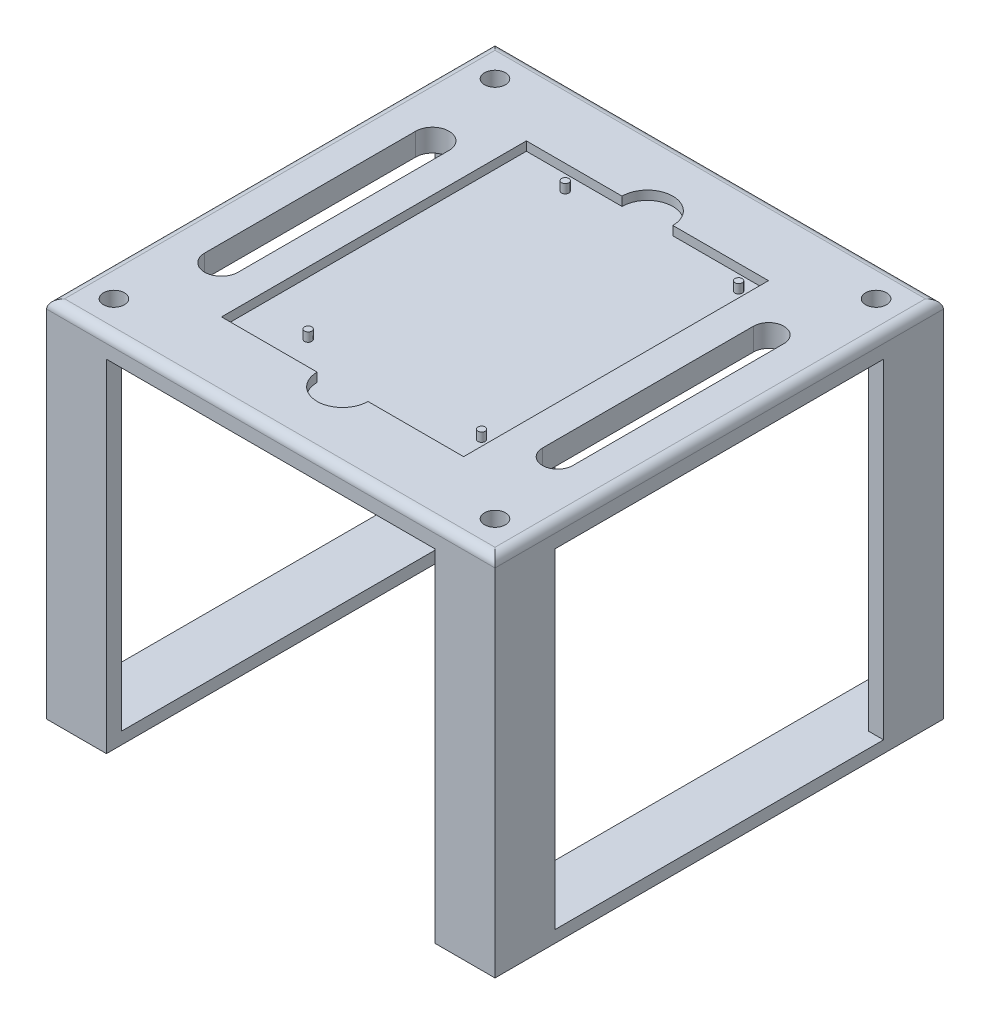
SolidWorks part; units mm, degrees
ref_plane "Front Plane" through (0, 0, 0) normal (0, 0, 1) x (1, 0, 0)
ref_plane "Top Plane" through (0, 0, 0) normal (0, 1, 0) x (1, 0, 0)
ref_plane "Right Plane" through (0, 0, 0) normal (1, 0, 0) x (0, 0, -1)
sketch "Sketch1" plane through (0, 0, 0) normal (0, 1, 0) x (1, 0, 0)
  line L1 (-75, 75) -> (75, 75)
  line L2 (-75, 75) -> (-75, -75)
  line L3 (-75, -75) -> (75, -75)
  line L4 (75, 75) -> (75, -75)
  line L5 (-75, 75) -> (75, -75) construction
  line L6 (-75, -75) -> (75, 75) construction
  point P0 (0, 0)
extrude "Boss-Extrude1" add sketch "Sketch1" along normal blind 7.5
sketch "Sketch2" plane through (0, 0, 0) normal (0, -1, 0) x (1, 0, 0)
  line L0 (-75, 70) -> (-70, 70) construction
  line L13 (-75, 75) -> (-55, 75)
  line L14 (-75, 75) -> (-75, 55)
  line L21 (-75, 55) -> (-70, 55)
  line L22 (-70, 55) -> (-70, 70)
  line L23 (-70, 70) -> (-55, 70)
  line L24 (-55, 70) -> (-55, 75)
  line L25 (75, 75) -> (54.9562, 75)
  line L26 (-75, 75) -> (75, 75) construction
  line L27 (54.9562, 75) -> (54.9562, 70)
  line L28 (54.9562, 70) -> (69.9502, 70)
  line L29 (69.9502, 70) -> (69.9502, 55)
  line L30 (69.9502, 55) -> (75, 55)
  line L31 (75, 75) -> (75, -75) construction
  line L32 (75, 55) -> (75, 75)
  line L33 (-75, -75) -> (-55, -75)
  line L34 (75, -75) -> (-75, -75) construction
  line L35 (-55, -75) -> (-55, -69.9766)
  line L36 (-55, -69.9766) -> (-70, -69.9766)
  line L37 (-70, -69.9766) -> (-70, -55.0007)
  line L38 (-70, -55.0007) -> (-75, -55.0007)
  line L39 (-75, -75) -> (-75, 75) construction
  line L40 (-75, -55.0007) -> (-75, -75)
  line L41 (75, -75) -> (54.9562, -75)
  line L42 (54.9562, -75) -> (54.9562, -69.9766)
  line L43 (54.9562, -69.9766) -> (69.9502, -69.9766)
  line L44 (69.9502, -69.9766) -> (69.9502, -55.0007)
  line L45 (69.9502, -55.0007) -> (75, -55.0007)
  line L46 (75, -55.0007) -> (75, -75)
extrude "Boss-Extrude2" add sketch "Sketch2" along normal blind 114.3
fillet "Fillet1" radius 3 4 edges at (0, 7.5, 75) (-75, 7.5, 0) (0, 7.5, -75) (75, 7.5, 0)
sketch "Sketch3" plane through (0, -114.3, 0) normal (0, -1, 0) x (1, 0, 0)
  line L17 (75, -75) -> (54.9562, -75)
  line L18 (75, -75) -> (75, 75)
  line L19 (75, 75) -> (54.9562, 75)
  line L20 (54.9562, -75) -> (54.9562, 75)
  line L21 (-75, 75) -> (-55, 75)
  line L22 (-75, 75) -> (-75, -75)
  line L23 (-75, -75) -> (-55, -75)
  line L24 (-55, 75) -> (-55, -75)
extrude "Boss-Extrude3" add sketch "Sketch3" against normal blind 4
sketch "Sketch5" plane through (0, 7.5, 0) normal (0, 1, 0) x (1, 0, 0)
  line L1 (-40.5, 51) -> (40.5, 51)
  line L2 (-40.5, 51) -> (-40.5, -51)
  line L3 (-40.5, -51) -> (40.5, -51)
  line L4 (40.5, 51) -> (40.5, -51)
  line L5 (-40.5, 51) -> (40.5, -51) construction
  line L6 (-40.5, -51) -> (40.5, 51) construction
  point P0 (0, 0)
extrude "Cut-Extrude1" cut sketch "Sketch5" against normal blind 3
sketch "Sketch6" plane through (0, 7.5, 0) normal (0, 1, 0) x (1, 0, 0)
  line L0 (-40.5, 0) -> (-72, 0) construction
  line L1 (-40.5, 51) -> (-40.5, -51) construction
  line L2 (-72, 72) -> (-72, -72) construction
  line L3 (-56.25, 35.2997) -> (-56.25, -35.2997) construction
  line L4 (-50.6741, 35.2997) -> (-50.6741, -35.2997)
  line L5 (-61.8259, 35.2997) -> (-61.8259, -35.2997)
  line L6 (40.5, 0) -> (72, 0) construction
  line L7 (40.5, -51) -> (40.5, 51) construction
  line L8 (72, -72) -> (72, 72) construction
  line L9 (56.25, 35.2997) -> (56.25, -35.2997) construction
  line L10 (61.3259, 35.2997) -> (61.3259, -35.2997)
  line L11 (51.1741, 35.2997) -> (51.1741, -35.2997)
  arc A0 (-50.6741, 35.2997) -> (-61.8259, 35.2997) centre (-56.25, 35.2997) ccw
  arc A1 (-61.8259, -35.2997) -> (-50.6741, -35.2997) centre (-56.25, -35.2997) ccw
  arc A2 (61.3259, 35.2997) -> (51.1741, 35.2997) centre (56.25, 35.2997) ccw
  arc A3 (51.1741, -35.2997) -> (61.3259, -35.2997) centre (56.25, -35.2997) ccw
  point P8 (-56.25, 0)
  point P21 (56.25, 0)
extrude "Cut-Extrude3" cut sketch "Sketch6" against normal up to next
sketch "Sketch7" plane through (0, 4.5, 0) normal (0, 1, 0) x (1, 0, 0)
  line L0 (39.5, 50) -> (39.5, 46) construction
  line L5 (39.5, 46) -> (35.5, 46) construction
  line L6 (-39.5, 50) -> (39.5, 50) construction
  line L7 (-39.5, 50) -> (-39.5, -50) construction
  line L8 (-39.5, -50) -> (39.5, -50) construction
  line L9 (39.5, 50) -> (39.5, -50) construction
  line L10 (35.5, 46) -> (-22.5, 46) construction
  line L11 (35.5, 46) -> (35.5, -40) construction
  line L12 (35.5, -40) -> (-22.5, -40) construction
  circle A0 centre (35.5, 46) radius 1.225
  circle A1 centre (-22.5, 46) radius 1.225
  circle A2 centre (-22.5, -40) radius 1.225
  circle A3 centre (35.5, -40) radius 1.225
  point P0 (0, 0)
  dimension "D1" = 4
extrude "Boss-Extrude4" add sketch "Sketch7" along normal blind 3
sketch "Sketch8" plane through (0, 7.5, 0) normal (0, 1, 0) x (1, 0, 0)
  line L1 (-63.75, 63.75) -> (63.75, 63.75) construction
  line L2 (-63.75, 63.75) -> (-63.75, -63.75) construction
  line L3 (-63.75, -63.75) -> (63.75, -63.75) construction
  line L4 (63.75, 63.75) -> (63.75, -63.75) construction
  line L5 (-63.75, 63.75) -> (63.75, -63.75) construction
  line L6 (-63.75, -63.75) -> (63.75, 63.75) construction
  circle A0 centre (-63.75, -63.75) radius 3.5
  circle A1 centre (63.75, -63.75) radius 3.5
  circle A2 centre (-63.75, 63.75) radius 3.5
  circle A3 centre (63.75, 63.75) radius 3.5
  point P0 (0, 0)
extrude "Cut-Extrude4" cut sketch "Sketch8" against normal up to surface (7.5 mm away) up to face at (-56.25, 0, 0)
sketch "Sketch9" plane through (0, 0, 0) normal (0, -1, 0) x (1, 0, 0)
  circle A0 centre (-63.75, 63.75) radius 5
  circle A1 centre (-63.75, 63.75) radius 3.5
  circle A2 centre (63.75, 63.75) radius 3.5
  circle A3 centre (63.75, 63.75) radius 5
  circle A4 centre (63.75, -63.75) radius 3.5
  circle A5 centre (63.75, -63.75) radius 5
  circle A6 centre (-63.75, -63.75) radius 3.5
  circle A7 centre (-63.75, -63.75) radius 5
extrude "Boss-Extrude5" add sketch "Sketch9" along normal blind 6
sketch "Sketch10" plane through (0, 7.5, 0) normal (0, 1, 0) x (1, 0, 0)
  line L0 (40.5, 51) -> (-40.5, 51) construction
  line L1 (-40.5, -51) -> (40.5, -51) construction
  circle A0 centre (0, 51) radius 8.5
  circle A1 centre (0, -51) radius 8.5
extrude "Cut-Extrude5" cut sketch "Sketch10" against normal up to surface (3 mm away) up to face at (35.5, 4.5, 41.225)
